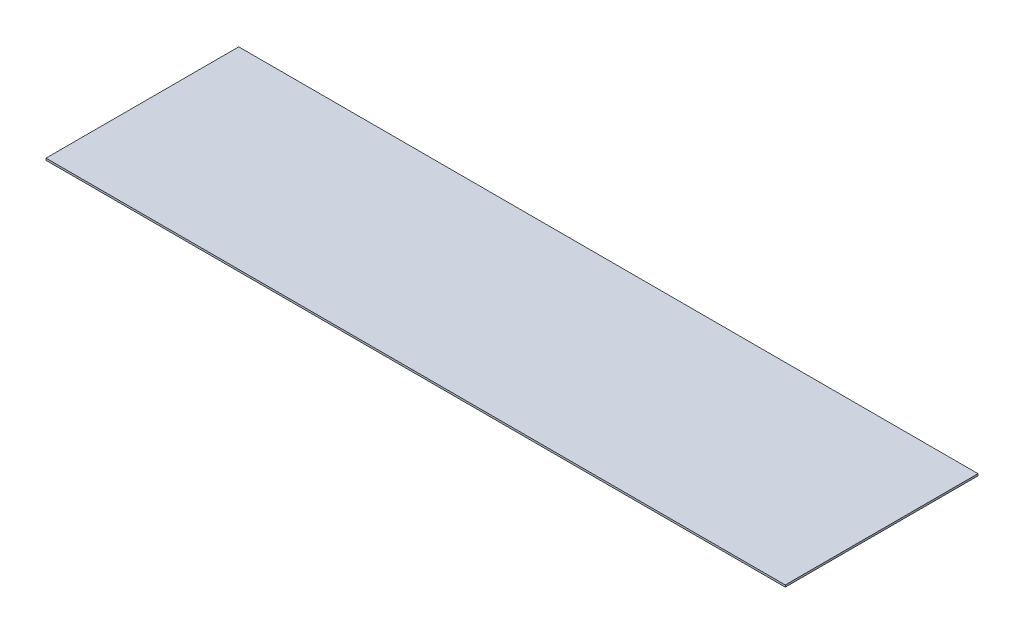
SolidWorks part; units mm, degrees
material "PE High Density"
ref_plane "Front Plane" through (0, 0, 0) normal (0, 0, 1) x (1, 0, 0)
ref_plane "Top Plane" through (0, 0, 0) normal (0, 1, 0) x (1, 0, 0)
ref_plane "Right Plane" through (0, 0, 0) normal (1, 0, 0) x (0, 0, -1)
sketch "Sketch1" plane through (0, 0, 0) normal (0, 1, 0) x (1, 0, 0)
  line L1 (0, 0) -> (1212.85, 0)
  line L2 (0, 0) -> (0, 316.23)
  line L3 (0, 316.23) -> (1212.85, 316.23)
  line L4 (1212.85, 0) -> (1212.85, 316.23)
  dimension "D1" = 1212.85
  dimension "D2" = 316.23
extrude "Boss-Extrude1" add sketch "Sketch1" along normal blind 3.175
